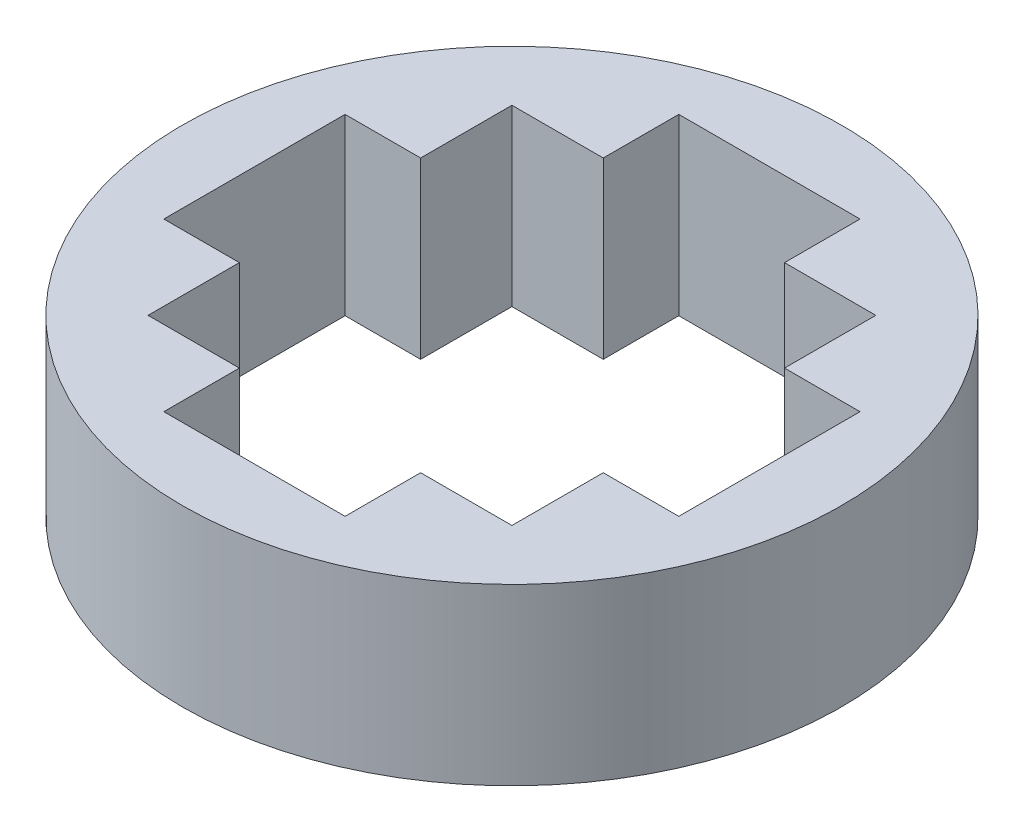
SolidWorks part; units mm, degrees
ref_plane "Front Plane" through (0, 0, 0) normal (0, 0, 1) x (1, 0, 0)
ref_plane "Top Plane" through (0, 0, 0) normal (0, 1, 0) x (1, 0, 0)
ref_plane "Right Plane" through (0, 0, 0) normal (1, 0, 0) x (0, 0, -1)
other "Default"
sketch "Sketch1" plane through (0, 0, 0) normal (0, 1, 0) x (1, 0, 0)
  line L0 (-6.6, 18.75) -> (6.6, 18.75)
  line L1 (6.6, 18.75) -> (6.6, 13.25)
  line L2 (6.6, 13.25) -> (13.25, 13.25)
  line L3 (13.25, 13.25) -> (13.25, 6.6)
  line L4 (13.25, 6.6) -> (18.75, 6.6)
  line L5 (18.75, 6.6) -> (18.75, -6.6)
  line L6 (18.75, -6.6) -> (13.25, -6.6)
  line L7 (13.25, -6.6) -> (13.25, -13.25)
  line L8 (13.25, -13.25) -> (6.6, -13.25)
  line L9 (6.6, -13.25) -> (6.6, -18.75)
  line L10 (6.6, -18.75) -> (-6.6, -18.75)
  line L11 (-6.6, -18.75) -> (-6.6, -13.25)
  line L12 (-6.6, -13.25) -> (-13.25, -13.25)
  line L13 (-13.25, -13.25) -> (-13.25, -6.6)
  line L14 (-13.25, -6.6) -> (-18.75, -6.6)
  line L15 (-18.75, -6.6) -> (-18.75, 6.6)
  line L16 (-18.75, 6.6) -> (-13.25, 6.6)
  line L17 (-13.25, 6.6) -> (-13.25, 13.25)
  line L18 (-13.25, 13.25) -> (-6.6, 13.25)
  line L19 (-6.6, 13.25) -> (-6.6, 18.75)
  circle A0 centre (0, 0) radius 24
  point P17 (-18.75, 0)
  point P24 (0, -18.75)
  dimension "OD" = 48
  dimension "Outer" = 13.2
  dimension "Side" = 5.5
  dimension "Inner" = 6.65
extrude "Boss-Extrude1" add sketch "Sketch1" along normal mid plane 12.7
sketch "Sketch2" plane through (0, 6.35, 0) normal (0, 1, 0) x (1, 0, 0)
  line L0 (0, 0) -> (-12.4413, 20.5235) construction
  line L1 (-8.0321, 13.25) -> (-12.4413, 20.5235) construction
  line L2 (-6.6, 13.25) -> (-13.25, 13.25) construction
  line L3 (-10.2367, 16.8867) -> (-10.2367, 13.25) construction
  line L4 (-10.2367, 16.8867) -> (-6.6, 16.8867) construction
  line L5 (-6.6, 18.75) -> (-6.6, 13.25) construction
  circle A0 centre (-10.2367, 16.8867) radius 1.5
  circle A1 centre (0, 0) radius 24 construction
  circle A2 centre (16.8867, 10.2367) radius 1.5
  circle A3 centre (10.2367, -16.8867) radius 1.5
  circle A4 centre (-16.8867, -10.2367) radius 1.5
  point P23 (0, 0)
  dimension "Hole" = 3
  dimension "D2" = 4
extrude "Holes" [suppressed] cut sketch "Sketch2" against normal through all
